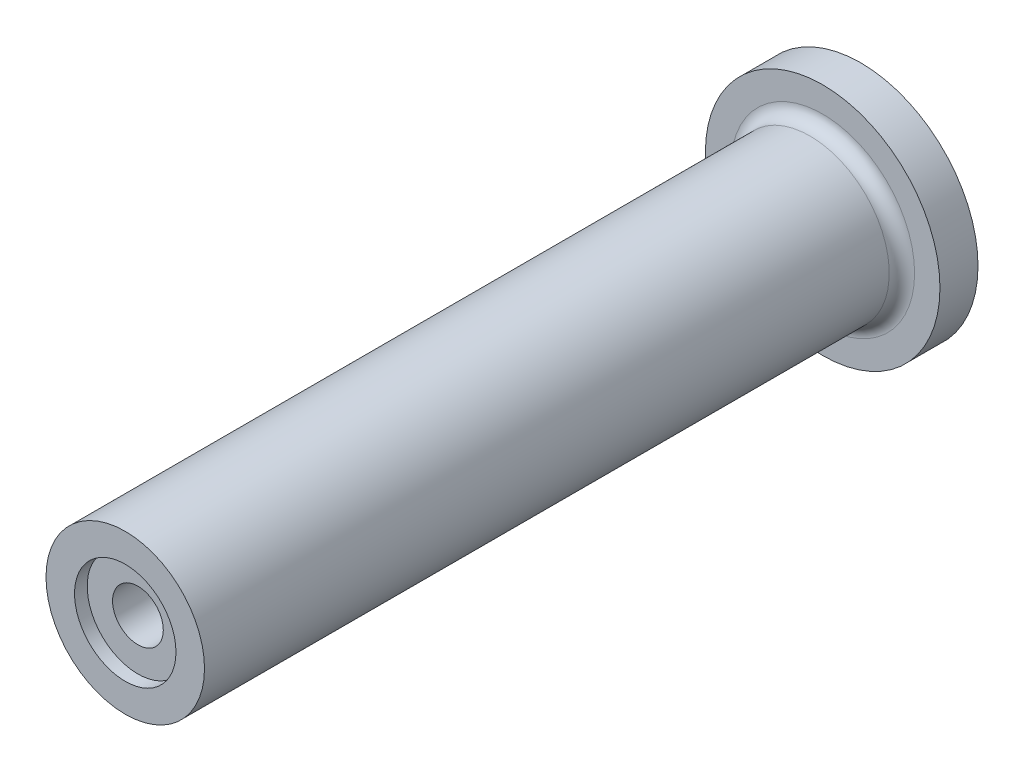
SolidWorks part; units mm, degrees
material "AISI 1020"
ref_plane "前视基准面" through (0, 0, 0) normal (0, 0, 1) x (1, 0, 0)
ref_plane "上视基准面" through (0, 0, 0) normal (0, 1, 0) x (1, 0, 0)
ref_plane "右视基准面" through (0, 0, 0) normal (1, 0, 0) x (0, 0, -1)
sketch "草图2" plane through (0, 0, 0) normal (0, 0, 1) x (1, 0, 0)
  circle A0 centre (0, 0) radius 12.5
  circle A1 centre (0, 0) radius 4
  dimension "D1" = 25
  dimension "D2" = 8
extrude "凸台-拉伸1" add sketch "草图2" along normal mid plane 110
sketch "草图3" plane through (0, 0, 55) normal (0, 0, 1) x (1, 0, 0)
  circle A0 centre (0, 0) radius 8
  dimension "D1" = 16
extrude "切除-拉伸1" cut sketch "草图3" against normal blind 2
sketch "草图4" plane through (0, 0, -55) normal (0, 0, -1) x (-1, 0, 0)
  circle A0 centre (0, 0) radius 8
  dimension "D1" = 16
extrude "切除-拉伸2" [suppressed] cut sketch "草图4" against normal blind 2
sketch "草图5" plane through (0, 0, -55) normal (0, 0, -1) x (-1, 0, 0)
  circle A0 centre (0, 0) radius 4 construction
  circle A1 centre (0, 0) radius 4
  circle A2 centre (0, 0) radius 18.5
  circle A3 centre (0, 0) radius 12.5 construction
  dimension "D1" = 6
extrude "凸台-拉伸2" add sketch "草图5" along normal blind 6
fillet "圆角1" radius 2 1 edges at (-12.5, 0, -55)
